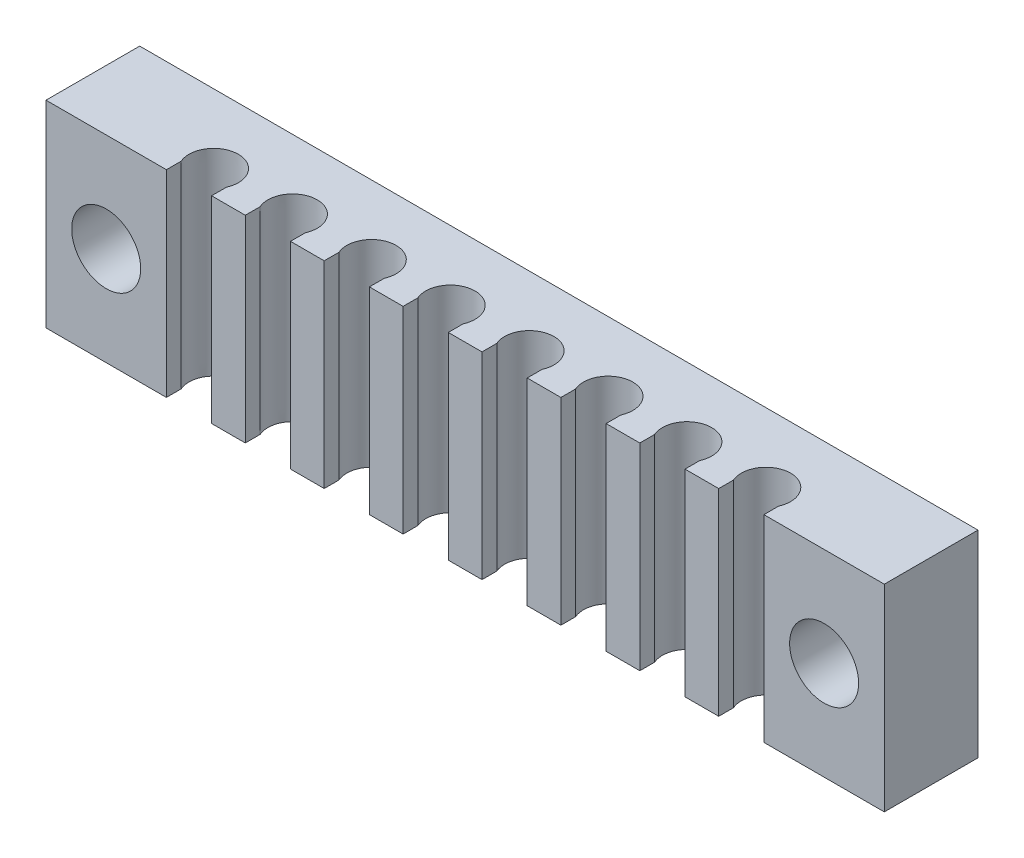
SolidWorks part; units mm, degrees
ref_plane "Front Plane" through (0, 0, 0) normal (0, 0, 1) x (1, 0, 0)
ref_plane "Top Plane" through (0, 0, 0) normal (0, 1, 0) x (1, 0, 0)
ref_plane "Right Plane" through (0, 0, 0) normal (1, 0, 0) x (0, 0, -1)
sketch "Sketch1" plane through (0, 0, 0) normal (0, 1, 0) x (1, 0, 0)
  line L0 (2.25, 0.5) -> (2.25, 0) construction
  line L1 (0, 0) -> (1.1044, 0)
  line L2 (0, 0) -> (0, 4)
  line L3 (0, 4) -> (17, 4)
  line L4 (17, 0) -> (17, 4)
  line L5 (1, 0.5) -> (0, 0.5) construction
  line L6 (3.5, 0.5) -> (5, 0.5) construction
  line L7 (-5, 0) -> (-5, -0.75)
  line L8 (0, 4) -> (-5, 4)
  line L9 (0, 4) -> (0, 0)
  line L10 (0, 0) -> (-5, 0)
  line L11 (-5, 4) -> (-5, 0)
  line L12 (-5, -0.75) -> (17, -0.75)
  line L13 (17, -0.75) -> (17, 0)
  line L14 (3.3956, 0) -> (5.1044, 0)
  line L15 (7.3956, 0) -> (9.1044, 0)
  line L16 (1.1044, 0) -> (1.1044, -0.75)
  line L17 (3.3956, 0) -> (3.3956, -0.75)
  line L18 (5.1044, 0) -> (5.1044, -0.75)
  line L19 (7.3956, 0) -> (7.3956, -0.75)
  line L20 (7.3956, 0) -> (9.1044, 0)
  line L21 (9.1044, 0) -> (9.1044, -0.75)
  line L22 (11.3956, 0) -> (11.3956, -0.75)
  line L23 (11.3956, 0) -> (13.1044, 0)
  line L24 (13.1044, 0) -> (13.1044, -0.75)
  line L25 (15.3956, 0) -> (15.3956, -0.75)
  line L26 (7.5, 0.5) -> (9, 0.5) construction
  line L27 (15.5, 0.5) -> (17, 0.5) construction
  line L28 (16.25, 0.5) -> (16.25, 4) construction
  line L29 (17.1044, 0) -> (17.1044, -0.75)
  line L30 (19.3956, 0) -> (19.3956, -0.75)
  line L31 (21.1044, 0) -> (21.1044, -0.75)
  line L32 (23.3956, 0) -> (23.3956, -0.75)
  line L33 (25.1044, 0) -> (25.1044, -0.75)
  line L34 (27.3956, 0) -> (27.3956, -0.75)
  line L35 (29.1044, 0) -> (29.1044, -0.75)
  line L36 (31.3956, 0) -> (31.3956, -0.75)
  line L37 (32.5, 4) -> (15.5, 4)
  line L38 (37.5, -0.75) -> (15.5, -0.75)
  line L39 (37.5, 0) -> (37.5, -0.75)
  line L40 (37.5, 4) -> (37.5, 0)
  line L41 (32.5, 4) -> (37.5, 4)
  line L42 (11.3956, 0) -> (13.1044, 0)
  line L43 (15.3956, 0) -> (17, 0)
  arc A0 (3.3956, 0) -> (1.1044, 0) centre (2.25, 0.5) ccw
  arc A1 (7.3956, 0) -> (5.1044, 0) centre (6.25, 0.5) ccw
  arc A2 (11.3956, 0) -> (9.1044, 0) centre (10.25, 0.5) ccw
  arc A3 (15.3956, 0) -> (13.1044, 0) centre (14.25, 0.5) ccw
  arc A4 (17.1044, 0) -> (19.3956, 0) centre (18.25, 0.5) cw
  arc A5 (21.1044, 0) -> (23.3956, 0) centre (22.25, 0.5) cw
  arc A6 (25.1044, 0) -> (27.3956, 0) centre (26.25, 0.5) cw
  arc A7 (29.1044, 0) -> (31.3956, 0) centre (30.25, 0.5) cw
  dimension "D2" = 2.5
  dimension "D7" = 1.5
  dimension "D10" = 1.5
  dimension "D1" = 4
  dimension "D3" = 0.5
  dimension "D4" = 1
  dimension "D5" = 17
  dimension "D8" = 5
  dimension "D9" = 3
  dimension "D6" = 2
extrude "Boss-Extrude1" add sketch "Sketch1" along normal blind 10 contours L8 L11 L10 L2 | A1 L1 L4 L3 L2 A0 | L16 L1 L10 L7 L12 | L18 L14 L17 L12 | L15 L19 L12 L13 | L24 L15 L22 L12 | L15 L25 L12 L13 | L35 A7 L36 L38 L39 L40 L41 L37 L4 A4 L30 L31 A5 L32 L33 A6 L34 | L29 A4 L4 L13 L38
sketch "Sketch4" plane through (0, 0, 0.75) normal (0, 0, 1) x (1, 0, 0)
  line L0 (-5, 10) -> (1.1044, 0) construction
  line L1 (16.25, 10) -> (16.25, 0) construction
  line L2 (17.1044, 10) -> (15.3956, 10) construction
  line L3 (17.1044, 0) -> (15.3956, 0) construction
  circle A0 centre (-1.9478, 5) radius 1.75
  circle A1 centre (34.4478, 5) radius 1.75
  dimension "D1" = 3.5
extrude "Cut-Extrude2" cut sketch "Sketch4" against normal through all
